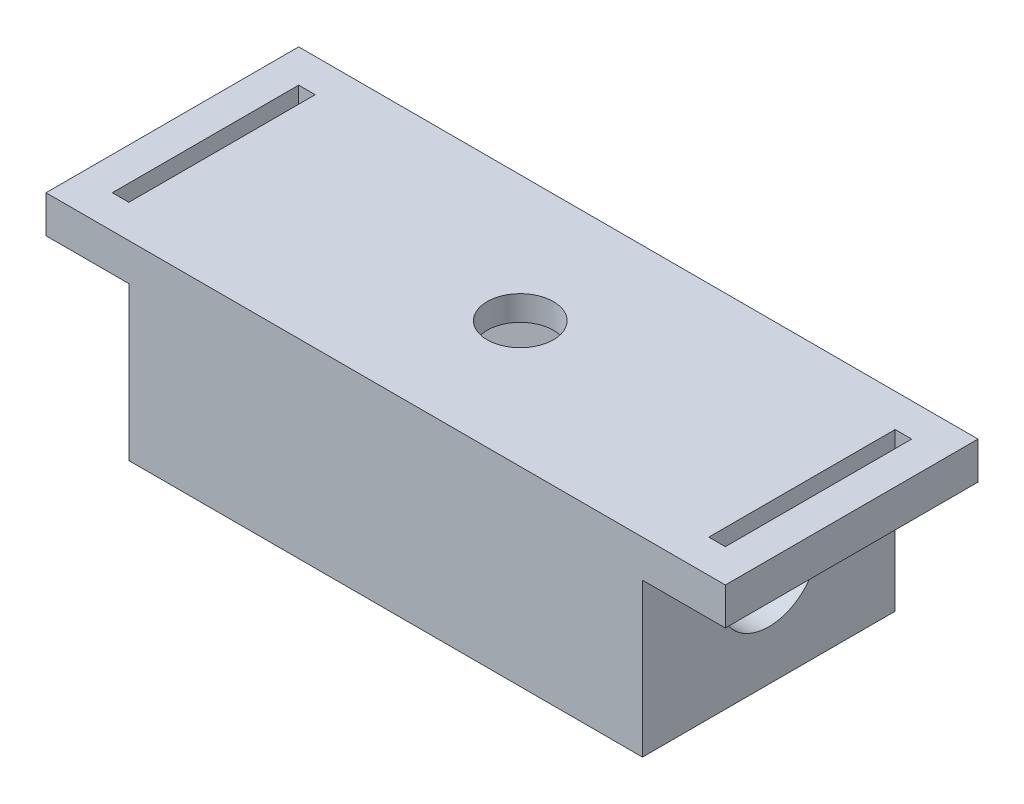
SolidWorks part; units mm, degrees
ref_plane "前视基准面" through (0, 0, 0) normal (0, 0, 1) x (1, 0, 0)
ref_plane "上视基准面" through (0, 0, 0) normal (0, 1, 0) x (1, 0, 0)
ref_plane "右视基准面" through (0, 0, 0) normal (1, 0, 0) x (0, 0, -1)
sketch "草图1" plane through (0, 0, 0) normal (0, 1, 0) x (1, 0, 0)
  line L0 (-28.6129, 7.5383) -> (-28.6129, -22.9617)
  line L1 (-24.6129, 3.5383) -> (33.3871, 3.5383)
  line L2 (-24.6129, 3.5383) -> (-24.6129, -18.9617)
  line L3 (-24.6129, -18.9617) -> (33.3871, -18.9617)
  line L4 (33.3871, 3.5383) -> (33.3871, -18.9617)
  line L5 (-28.6129, -22.9617) -> (37.3871, -22.9617)
  line L6 (37.3871, 7.5383) -> (37.3871, -22.9617)
  line L7 (-28.6129, 7.5383) -> (37.3871, 7.5383)
  dimension "D1" = 22.5
  dimension "D2" = 58
  dimension "D3" = 4
extrude "凸台-拉伸1" add sketch "草图1" along normal blind 27
sketch "草图2" plane through (0, 27, 0) normal (0, 1, 0) x (1, 0, 0)
  line L0 (4.3871, 7.5383) -> (4.3871, -22.9617) construction
  line L1 (37.3871, 7.5383) -> (-28.6129, 7.5383) construction
  line L2 (-28.6129, -22.9617) -> (37.3871, -22.9617) construction
  line L4 (-28.6129, 7.5383) -> (37.3871, 7.5383)
  line L5 (-28.6129, 7.5383) -> (-28.6129, -22.9617)
  line L6 (-28.6129, -22.9617) -> (37.3871, -22.9617)
  line L7 (37.3871, 7.5383) -> (37.3871, -22.9617)
extrude "凸台-拉伸2" add sketch "草图2" against normal blind 3
sketch "草图3" plane through (0, 27, 0) normal (0, 1, 0) x (1, 0, 0)
  line L0 (-28.6129, 7.5383) -> (7.3871, 7.5383) construction
  line L1 (37.3871, 7.5383) -> (-28.6129, 7.5383) construction
  line L2 (7.3871, 7.5383) -> (7.3871, -22.9617) construction
  line L3 (-28.6129, -22.9617) -> (37.3871, -22.9617) construction
  circle A0 centre (7.3871, -7.7117) radius 4
extrude "切除-拉伸1" cut sketch "草图3" against normal through all
sketch "草图4" plane through (33.3871, 0, 0) normal (-1, 0, 0) x (0, 0, 1)
  line L0 (7.7117, 24) -> (7.7117, 16) construction
  line L1 (18.9617, 24) -> (-3.5383, 24) construction
  circle A0 centre (7.7117, 16) radius 6
extrude "切除-拉伸2" cut sketch "草图4" against normal blind 11
sketch "草图5" plane through (0, 0, 0) normal (0, -1, 0) x (1, 0, 0)
  line L0 (37.3871, -7.5383) -> (-28.6129, -7.5383) construction
  line L1 (-28.6129, 22.9617) -> (-24.6129, 22.9617)
  line L2 (-28.6129, 22.9617) -> (-28.6129, -7.5383)
  line L3 (-28.6129, -7.5383) -> (-24.6129, -7.5383)
  line L4 (-24.6129, 22.9617) -> (-24.6129, -7.5383)
extrude "切除-拉伸3" cut sketch "草图5" against normal through all
sketch "草图6" plane through (37.3871, 0, 0) normal (1, 0, 0) x (0, 0, -1)
  line L0 (-22.9617, 27) -> (-22.9617, 0) construction
  line L1 (7.5383, 27) -> (-22.9617, 27)
  line L2 (7.5383, 27) -> (7.5383, 22.5)
  line L3 (7.5383, 22.5) -> (-22.9617, 22.5)
  line L4 (-22.9617, 27) -> (-22.9617, 22.5)
  dimension "D1" = 4.5
extrude "凸台-拉伸3" add sketch "草图6" along normal blind 10
sketch "草图7" plane through (0, 22.5, 0) normal (0, -1, 0) x (1, 0, 0)
  line L0 (41.3871, 18.9617) -> (41.3871, -3.5383)
  line L1 (37.3871, 22.9617) -> (47.3871, 22.9617)
  line L2 (37.3871, 22.9617) -> (37.3871, -7.5383)
  line L3 (37.3871, -7.5383) -> (47.3871, -7.5383)
  line L4 (47.3871, 22.9617) -> (47.3871, -7.5383)
  line L5 (41.3871, -3.5383) -> (43.3871, -3.5383)
  line L6 (43.3871, 18.9617) -> (43.3871, -3.5383)
  line L7 (41.3871, 18.9617) -> (43.3871, 18.9617)
  dimension "D1" = 4
extrude "切除-拉伸4" cut sketch "草图7" against normal blind 10 contours L6 L5 L0 L7
sketch "草图8" plane through (-24.6129, 0, 0) normal (-1, 0, 0) x (0, 0, 1)
  line L0 (22.9617, 27) -> (22.9617, 0) construction
  line L1 (-7.5383, 27) -> (22.9617, 27)
  line L2 (-7.5383, 27) -> (-7.5383, 22.5)
  line L3 (-7.5383, 22.5) -> (22.9617, 22.5)
  line L4 (22.9617, 27) -> (22.9617, 22.5)
extrude "凸台-拉伸4" add sketch "草图8" along normal blind 10
sketch "草图9" plane through (0, 22.5, 0) normal (0, -1, 0) x (1, 0, 0)
  line L0 (-30.6129, 18.9617) -> (-30.6129, -3.5383)
  line L1 (-34.6129, 22.9617) -> (-24.6129, 22.9617)
  line L2 (-34.6129, 22.9617) -> (-34.6129, -7.5383)
  line L3 (-34.6129, -7.5383) -> (-24.6129, -7.5383)
  line L4 (-24.6129, 22.9617) -> (-24.6129, -7.5383)
  line L5 (-30.6129, -3.5383) -> (-28.6129, -3.5383)
  line L6 (-28.6129, 18.9617) -> (-28.6129, -3.5383)
  line L7 (-30.6129, 18.9617) -> (-28.6129, 18.9617)
  dimension "D1" = 4
extrude "切除-拉伸5" cut sketch "草图9" against normal blind 10 contours L0 L5 L6 L7
sketch "草图10" plane through (0, 0, 0) normal (0, -1, 0) x (1, 0, 0)
  line L1 (-24.6129, 22.9617) -> (37.3871, 22.9617)
  line L2 (-24.6129, 22.9617) -> (-24.6129, -7.5383)
  line L3 (-24.6129, -7.5383) -> (37.3871, -7.5383)
  line L4 (37.3871, 22.9617) -> (37.3871, -7.5383)
extrude "切除-拉伸6" cut sketch "草图10" against normal blind 4
